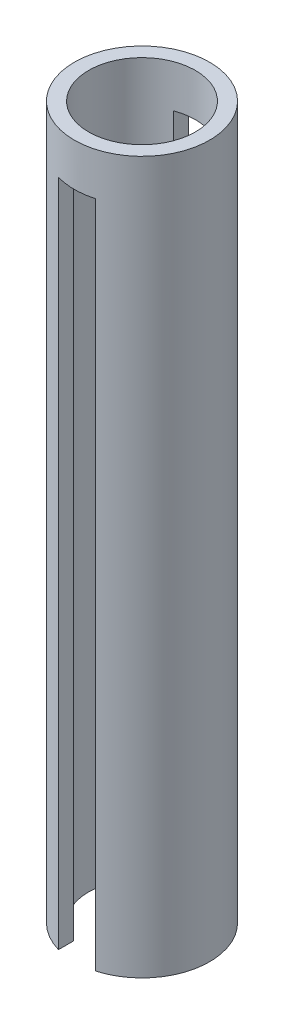
SolidWorks part; units mm, degrees
ref_plane "Front Plane" through (0, 0, 0) normal (0, 0, 1) x (1, 0, 0)
ref_plane "Top Plane" through (0, 0, 0) normal (0, 1, 0) x (1, 0, 0)
ref_plane "Right Plane" through (0, 0, 0) normal (1, 0, 0) x (0, 0, -1)
sketch "Sketch1" plane through (0, 0, 0) normal (0, 1, 0) x (1, 0, 0)
  circle A0 centre (0, 0) radius 7.5
  circle A1 centre (0, 0) radius 9.5
  dimension "D1" = 15
  dimension "D2" = 2
extrude "Boss-Extrude1" add sketch "Sketch1" along normal blind 100
ref_plane "Plane1" through (0, 0, 20) normal (0, 0, 1) x (1, 0, 0)
sketch "Sketch2" plane through (0, 0, 20) normal (0, 0, 1) x (1, 0, 0)
  line L0 (0, 0) -> (0, 94) construction
  line L3 (2.6, 0) -> (2.6, 94)
  line L4 (9.5, 94) -> (-9.5, 94)
  line L5 (9.5, 94) -> (-9.5, 94) construction
  line L6 (-2.6, 0) -> (-2.6, 94)
  line L7 (-2.6, 0) -> (2.6, 0)
  line L8 (-2.6, 94) -> (2.6, 94)
  dimension "D1" = 6
  dimension "D2" = 2.6
  dimension "D3" = 2.6
extrude "Cut-Extrude1" cut sketch "Sketch2" against normal blind 100
